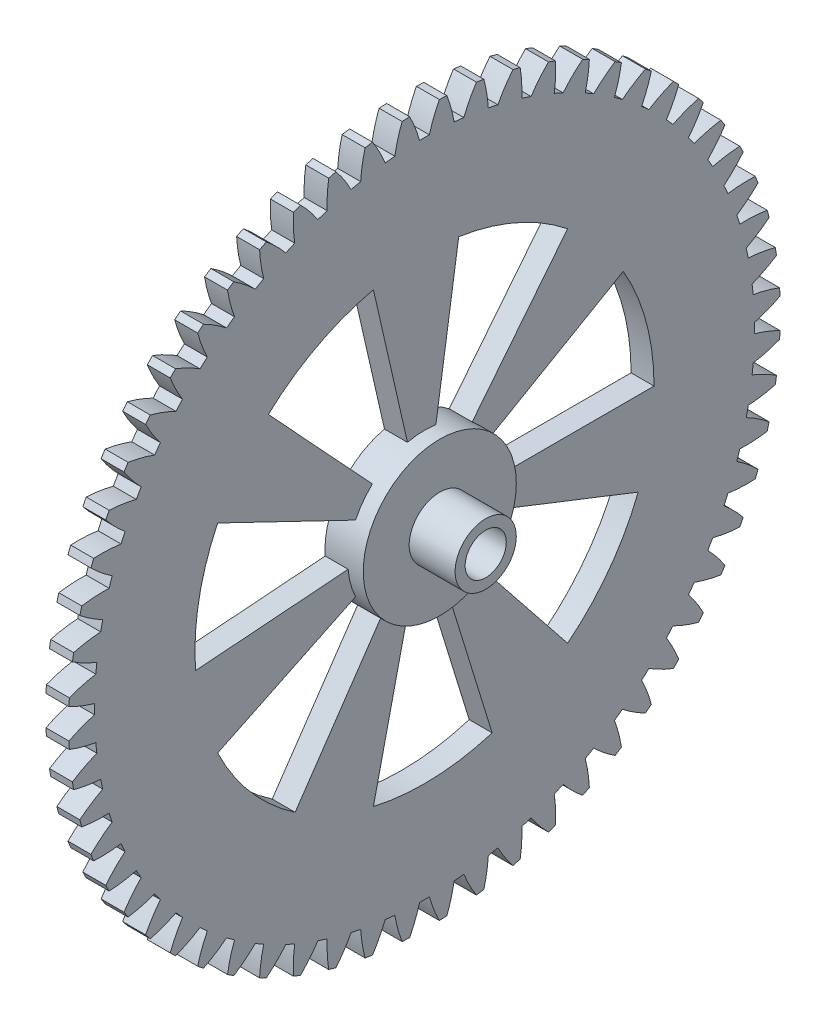
SolidWorks part; units mm, degrees
ref_plane "Plane1" through (0, 0, 0) normal (0, 0, 1) x (1, 0, 0)
ref_plane "Plane2" through (0, 0, 0) normal (0, 1, 0) x (1, 0, 0)
ref_plane "Plane3" through (0, 0, 0) normal (1, 0, 0) x (0, 0, -1)
sketch "HoldingSke" plane through (0, 0, 0) normal (0, 1, 0) x (1, 0, 0)
  line L0 (0, 0) -> (0.3333, -0.5774)
  line L1 (-15, 0) -> (100, 0) construction
  line L2 (0, 0) -> (-2.1039, 2.3779)
  line L3 (0, 0) -> (-11.863, 4.5341)
  line L4 (0, 0) -> (4.318, 7.479)
  line L5 (0, 0) -> (-46.8476, -17.4728)
  line L6 (0, 0) -> (-2.4869, -1.6779)
  line L7 (-2.1039, 2.3779) -> (8.6586, 51.2059)
  line L8 (-76.2, 54.61) -> (-76.1, 54.61)
  line L9 (-71.009, 38.7566) -> (-53.1078, 45.2721)
  line L10 (-76.2, 71.12) -> (104.1128, 71.12)
  line L11 (0, 0) -> (-3, 0)
  line L12 (-76.2, 101.6) -> (-76.147, 101.6)
  line L13 (24.9733, 27.94) -> (52.9518, 28.4284)
  line L14 (24.9733, 27.94) -> (24.9743, 27.94)
  line L15 (24.9733, 27.94) -> (100.4006, 29.5858)
  line L16 (-63.627, -1.5) -> (-12.827, -1.5)
  circle A0 centre (0, 0) radius 0.5
  circle A1 centre (0, 0) radius 37.5
  circle A2 centre (0, 0) radius 37.5
  circle A3 centre (0, 0) radius 0.5
  dimension "MHD" = 75
  dimension "Hub_dia" = 75
  dimension "Bore" = 1
  dimension "MBD" = 1
  dimension "Num_teeth" = 60
  dimension "Pitch" = 0.6667
  dimension "Overall_len" = 50
  dimension "Show_teeth" = 60
  dimension "Thickness" = 3
  dimension "OAL" = 50.0001
  dimension "T_dim" = 0.1
  dimension "Ap" = 20
  dimension "H" = 19.05
  dimension "Pitch_radius" = 180.3128
  dimension "Width" = 3
  dimension "Backlash" = 0.053
  dimension "Addendum_fac" = 1
  dimension "Dedendum_fac" = 1.25
  dimension "Clearance_fac" = 0.25
  dimension "Dedendum_add" = 0.001
  dimension "Module" = 1.5
sketch "BasProSke" plane through (0, 0, 0) normal (0, 1, 0) x (1, 0, 0)
  line L0 (-10, 0) -> (60, 0) construction
  line L1 (0, 0) -> (0, 46.5)
  line L2 (0, 0) -> (3, 0)
  line L3 (3, 0) -> (3, 46.5)
  line L4 (3, 46.5) -> (0, 46.5)
  dimension "Thickness" = 3
  dimension "Diameter" = 93
revolve "Base-Revolve" add sketch "BasProSke" angle 360 about L0
sketch "TooCutSke" plane through (0, 0, 0) normal (1, 0, 0) x (0, 0, -1)
  line L1 (0, 0) -> (0, 107) construction
  line L2 (0, 0) -> (-1.2707, 44.9821) construction
  line L3 (0, 0) -> (-4.7089, 89.8505) construction
  line L4 (-1.2707, 44.9821) -> (-2.3544, 44.9253) construction
  arc A0 (0.6387, 43.1193) -> (-0.6387, 43.1193) centre (0, 0) ccw
  arc A1 (1.9554, 46.4843) -> (-1.9554, 46.4843) centre (0, 0) ccw
  circle A2 centre (0, 0) radius 45 construction
  circle A3 centre (0, 0) radius 42.2862 construction
  arc A4 (-0.6387, 43.1193) -> (-1.9554, 46.4843) centre (-17.9747, 38.2757) ccw
  arc A5 (1.9554, 46.4843) -> (0.6387, 43.1193) centre (17.9747, 38.2757) ccw
  dimension "Root_dia" = 86.248
  dimension "Overcut_dia" = 93.0508
  dimension "Pitch_dia" = 90
  dimension "Base_dia" = 84.5723
  dimension "Flank_rad" = 18
  dimension "Half_ang" = 3
  dimension "Half_CT" = 1.0852
extrude "ToothCut" cut sketch "TooCutSke" along normal through all
fillet "Breaks" [suppressed] radius 0.03
fillet "RootFillets" [suppressed] radius 0.376
pattern_circular "TeethCuts" count 60 every 6 about axis through (-10, 0, 0) along (1, 0, 0) of "ToothCut", "RootFillets", "Breaks"
sketch "HubNeaOneSke" plane through (0, 0, 0) normal (-1, 0, 0) x (0, 0, 1)
  circle A0 centre (0, 0) radius 37.5
  dimension "Diameter" = 75
extrude "HubNearOne" [suppressed] add sketch "HubNeaOneSke" along normal blind 47.0001
sketch "HubNeaBotSke" plane through (0, 0, 0) normal (-1, 0, 0) x (0, 0, 1)
  circle A0 centre (0, 0) radius 37.5
  dimension "Diameter" = 75
extrude "HubNearBoth" [suppressed] add sketch "HubNeaBotSke" along normal blind 23.5
ref_plane "FarPln" through (3, 0, 0) normal (1, 0, 0) x (0, 0, -1)
sketch "HubFarSke" plane through (3, 0, 0) normal (1, 0, 0) x (0, 0, -1)
  circle A0 centre (0, 0) radius 37.5
  dimension "Diameter" = 75
extrude "HubFar" [suppressed] add sketch "HubFarSke" along normal blind 23.5
sketch "BorSke" plane through (0, 0, 0) normal (1, 0, 0) x (0, 0, -1)
  circle A0 centre (0, 0) radius 0.5
  dimension "Diameter" = 1
extrude "Bore" cut sketch "BorSke" along normal mid plane 100.0001
sketch "KeySke" plane through (0, 0, 0) normal (1, 0, 0) x (0, 0, -1)
  line L0 (-0.05, 0) -> (-0.05, 0.6)
  line L1 (-0.05, 0.6) -> (0.05, 0.6)
  line L2 (0.05, 0.6) -> (0.05, 0)
  line L3 (0, 0) -> (0, 34) construction
  line L4 (-0.05, 0) -> (0.05, 0)
  dimension "Offset" = 0.6
  dimension "Width" = 0.1
extrude "Keyway" [suppressed] cut sketch "KeySke" along normal mid plane 100.0001
pattern_circular "Keyway2" [suppressed] count 2 every 90 about axis through (-10, 0, 0) along (1, 0, 0)
sketch "Sketch1" plane through (3, 0, 0) normal (1, 0, 0) x (0, 0, -1)
  circle A0 centre (0, 0) radius 6.4
  dimension "D1" = 12.8
extrude "Cut-Extrude1" cut sketch "Sketch1" against normal up to next
sketch "Sketch2" plane through (3, 0, 0) normal (1, 0, 0) x (0, 0, -1)
  circle A0 centre (0, 0) radius 37.0881 construction
sketch "Sketch3" plane through (3, 0, 0) normal (1, 0, 0) x (0, 0, -1)
  line L0 (0, 0) -> (30, 0) construction
  line L1 (0, 0) -> (25.9808, 15) construction
  line L2 (8.6603, 5) -> (25.9808, 15)
  line L3 (30, 0) -> (10, 0)
  line L4 (9.3087, -3.6534) -> (27.9262, -10.9602)
  line L5 (18.7047, -23.4549) -> (6.2349, -7.8183)
  line L6 (2.9476, -9.5557) -> (8.8427, -28.6672)
  line L7 (-6.6756, -29.2478) -> (-2.2252, -9.7493)
  line L8 (-5.6332, -8.2624) -> (-16.8996, -24.7872)
  line L9 (-27.0291, -13.0165) -> (-9.0097, -4.3388)
  line L10 (-9.972, -0.7473) -> (-29.9161, -2.2419)
  line L11 (-27.0291, 13.0165) -> (-9.0097, 4.3388)
  line L12 (-6.8017, 7.3305) -> (-20.4052, 21.9916)
  line L13 (-6.6756, 29.2478) -> (-2.2252, 9.7493)
  line L14 (1.4904, 9.8883) -> (4.4713, 29.6649)
  line L15 (18.7047, 23.4549) -> (6.2349, 7.8183)
  arc A0 (10, 0) -> (8.6603, 5) centre (0, 0) ccw
  arc A1 (30, 0) -> (25.9808, 15) centre (0, 0) ccw
  arc A2 (18.7047, -23.4549) -> (27.9262, -10.9602) centre (0, 0) ccw
  arc A3 (6.2349, -7.8183) -> (9.3087, -3.6534) centre (0, 0) ccw
  arc A4 (-6.6756, -29.2478) -> (8.8427, -28.6672) centre (0, 0) ccw
  arc A5 (-2.2252, -9.7493) -> (2.9476, -9.5557) centre (0, 0) ccw
  arc A6 (-27.0291, -13.0165) -> (-16.8996, -24.7872) centre (0, 0) ccw
  arc A7 (-9.0097, -4.3388) -> (-5.6332, -8.2624) centre (0, 0) ccw
  arc A8 (-27.0291, 13.0165) -> (-29.9161, -2.2419) centre (0, 0) ccw
  arc A9 (-9.0097, 4.3388) -> (-9.972, -0.7473) centre (0, 0) ccw
  arc A10 (-6.6756, 29.2478) -> (-20.4052, 21.9916) centre (0, 0) ccw
  arc A11 (-2.2252, 9.7493) -> (-6.8017, 7.3305) centre (0, 0) ccw
  arc A12 (18.7047, 23.4549) -> (4.4713, 29.6649) centre (0, 0) ccw
  arc A13 (6.2349, 7.8183) -> (1.4904, 9.8883) centre (0, 0) ccw
  point P32 (0, 0)
  dimension "D1" = 30
  dimension "D2" = 7
extrude "Cut-Extrude2" cut sketch "Sketch3" against normal up to next
sketch "Sketch4" plane through (3, 0, 0) normal (1, 0, 0) x (0, 0, -1)
  circle A0 centre (0, 0) radius 1.69 construction
  circle A1 centre (0, 0) radius 10
  circle A2 centre (0, 0) radius 2.69
  dimension "D1" = 3.38
  dimension "D2" = 1
extrude "Boss-Extrude1" add sketch "Sketch4" along normal blind 2
sketch "Sketch5" plane through (5, 0, 0) normal (1, 0, 0) x (0, 0, -1)
  circle A0 centre (0, 0) radius 2.69 construction
  circle A1 centre (0, 0) radius 2.69
  circle A2 centre (0, 0) radius 4
  dimension "D1" = 8
extrude "Boss-Extrude2" add sketch "Sketch5" along normal blind 6
equation "' \"Module@HoldingSke\" = 6.35"
equation "' \"Num_teeth@HoldingSke\" = 12"
equation "' \"Ap@HoldingSke\" =  20"
equation "' \"Ap@HoldingSke\" = 20"
equation "' \"Width@HoldingSke\" = 0.5 * 25.4"
equation "' \"Hub_dia@HoldingSke\"= 1 * 25.4"
equation "' \"Hub_dia@HoldingSke\" = 1 * 25.4"
equation "' \"Overall_len@HoldingSke\" = 1.0 * 25.4"
equation "' \"Bore@HoldingSke\" = 0.75 * 25.4"
equation "' \"T_dim@HoldingSke\" = 0.1 * 25.4"
equation "' \"Width@KeySke\" = 0.25 * 25.4"
equation "' \"Show_teeth@HoldingSke\" = 13"
equation "' \"Backlash@HoldingSke\" = 0.009 * 25.4"
equation "' \"Addendum_fac@HoldingSke\" = 1.0"
equation "' \"Dedendum_fac@HoldingSke\" = 1.25"
equation "' \"Dedendum_add@HoldingSke\" = 0.00005 * 25.4"
equation "' \"Clearance_fac@HoldingSke\" = 0.25"
equation "\"Pitch@HoldingSke\" = 1 / \"Module@HoldingSke\""
equation "\"Overcut_dia@TooCutSke\" = (\"Num_teeth@HoldingSke\" + 2 * \"Addendum_fac@HoldingSke\") / \"Pitch@HoldingSke\" + 0.002 * 25.4"
equation "\"Pitch_dia@TooCutSke\" = \"Num_teeth@HoldingSke\" / \"Pitch@HoldingSke\""
equation "\"Base_dia@TooCutSke\" = \"Num_teeth@HoldingSke\" / \"Pitch@HoldingSke\" * cos((\"Ap@HoldingSke\"  * 3.14159265 / 180))"
equation "\"Root_dia@TooCutSke\" = (\"Num_teeth@HoldingSke\" + 2) / \"Pitch@HoldingSke\" - 2 * (\"Addendum_fac@HoldingSke\" + \"Dedendum_fac@HoldingSke\") / \"Pitch@HoldingSke\" - \"Dedendum_add@HoldingSke\" * 2"
equation "\"Half_ang@TooCutSke\" = 180 / \"Num_teeth@HoldingSke\""
equation "\"Half_CT@TooCutSke\" = \"Num_teeth@HoldingSke\" / \"Pitch@HoldingSke\" * sin((3.14159265 / 2 / \"Num_teeth@HoldingSke\")) / 2 - 7 * \"Backlash@HoldingSke\" / 4"
equation "\"Flank_rad@TooCutSke\" = \"Num_teeth@HoldingSke\" / \"Pitch@HoldingSke\" / 5"
equation "\"Radius@RootFillets\" = \"Clearance_fac@HoldingSke\" / \"Pitch@HoldingSke\" + \"Dedendum_add@HoldingSke\""
equation "\"Break_rad@Breaks\" = 0.02 / \"Pitch@HoldingSke\""
equation "\"Thickness@HoldingSke\" = \"Width@HoldingSke\""
equation "\"OAL@HoldingSke\" = \"Thickness@HoldingSke\""
equation "\"MHD@HoldingSke\" = (\"Num_teeth@HoldingSke\" + 2) / \"Pitch@HoldingSke\" - 2 * (\"Addendum_fac@HoldingSke\" + \"Dedendum_fac@HoldingSke\")  / \"Pitch@HoldingSke\" - \"Dedendum_add@HoldingSke\" * 2"
equation "\"MBD@HoldingSke\" = (\"Num_teeth@HoldingSke\" + 2) / \"Pitch@HoldingSke\" - 2 * (\"Addendum_fac@HoldingSke\" + \"Dedendum_fac@HoldingSke\")  / \"Pitch@HoldingSke\" - \"Dedendum_add@HoldingSke\" * 2 - 0.002 * 25.4"
equation "\"MHD@HoldingSke\" = ((sgn( \"MHD@HoldingSke\" - \"Hub_dia@HoldingSke\" )-1)*( \"MHD@HoldingSke\" - \"Hub_dia@HoldingSke\" ))/-2+ \"Hub_dia@HoldingSke\""
equation "\"MBD@HoldingSke\" = ((sgn( \"MBD@HoldingSke\" - \"Bore@HoldingSke\" )-1)*( \"MBD@HoldingSke\" - \"Bore@HoldingSke\" ))/-2+ \"Bore@HoldingSke\""
equation "\"OAL@HoldingSke\" = ((sgn( \"OAL@HoldingSke\" - \"Overall_len@HoldingSke\" )+1)*( \"OAL@HoldingSke\" - \"Overall_len@HoldingSke\" ))/2 + \"Overall_len@HoldingSke\" + 0.000002 * 25.4"
equation "\"Num_teeth@TeethCuts\" = int( \"Show_teeth@HoldingSke\" ) + 1"
equation "\"Num_teeth@TeethCuts\" = ((sgn( \"Num_teeth@TeethCuts\" - \"Num_teeth@HoldingSke\" )-1)*( \"Num_teeth@TeethCuts\" - \"Num_teeth@HoldingSke\" ))/-2+ \"Num_teeth@HoldingSke\""
equation "\"Num_teeth@TeethCuts\" = ((sgn( \"Num_teeth@TeethCuts\" - 2.0)+1)*( \"Num_teeth@TeethCuts\" - 2.0))/2 +2.0"
equation "\"Angle@TeethCuts\" = 360.0 / \"Num_teeth@HoldingSke\""
equation "\"Diameter@BasProSke\" = (\"Num_teeth@HoldingSke\" + 2 * \"Addendum_fac@HoldingSke\") / \"Pitch@HoldingSke\""
equation "\"Thickness@BasProSke\"  = \"Thickness@HoldingSke\""
equation "' \"Fillet_rad@BasProSke\" =  \"Thickness@HoldingSke\" * 0.05"
equation "' \"Fillet_rad@BasProSke\" = \"Thickness@HoldingSke\" * 0.05"
equation "\"MHD@HoldingSke\" = ((sgn( \"MHD@HoldingSke\" - \"Root_dia@TooCutSke\" )-1)*( \"MHD@HoldingSke\" - \"Root_dia@TooCutSke\" ))/-2+ \"Root_dia@TooCutSke\""
equation "\"Diameter@HubNeaOneSke\" = \"MHD@HoldingSke\""
equation "\"Length@HubNearOne\" = \"OAL@HoldingSke\" - \"Thickness@BasProSke\""
equation "\"Diameter@HubNeaBotSke\" = \"MHD@HoldingSke\""
equation "\"Length@HubNearBoth\" = ( \"OAL@HoldingSke\" - \"Thickness@BasProSke\" ) / 2.0"
equation "\"Thickness@FarPln\" = \"Thickness@BasProSke\""
equation "\"Diameter@HubFarSke\" = \"MHD@HoldingSke\""
equation "\"Length@HubFar\" = ( \"OAL@HoldingSke\" - \"Thickness@BasProSke\" ) / 2.0"
equation "\"Diameter@BorSke\" = \"MBD@HoldingSke\""
equation "\"D1@Bore\" = \"OAL@HoldingSke\" * 2.0"
equation "\"D1@Keyway\" = \"OAL@HoldingSke\" * 2.0"
equation "\"Offset@KeySke\" = \"T_dim@HoldingSke\" + \"MBD@HoldingSke\" / 2.0"
